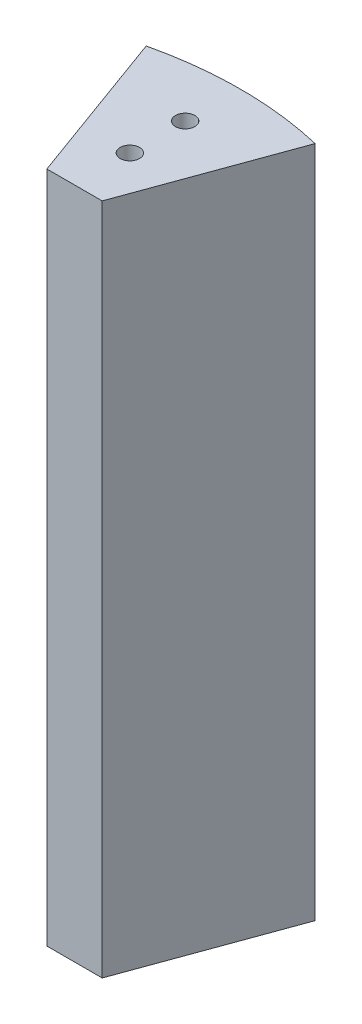
SolidWorks part; units mm, degrees
ref_plane "Front Plane" through (0, 0, 0) normal (0, 0, 1) x (1, 0, 0)
ref_plane "Top Plane" through (0, 0, 0) normal (0, 1, 0) x (1, 0, 0)
ref_plane "Right Plane" through (0, 0, 0) normal (1, 0, 0) x (0, 0, -1)
sketch "Sketch1" plane through (0, 0, 0) normal (0, 1, 0) x (1, 0, 0)
  line L0 (0, 0) -> (0, 66.5)
  line L1 (0, 0) -> (57.5907, -33.25)
  line L2 (0, 0) -> (-57.5907, -33.25)
  line L3 (5, 36.5) -> (-5, 36.5)
  line L4 (-5, 36.5) -> (-15.2722, 64.7226)
  line L5 (5, 36.5) -> (15.2722, 64.7226)
  line L6 (0, 66.5) -> (0, 56.5)
  line L7 (0, 56.5) -> (0, 46.5)
  line L8 (34.1099, -13.9199) -> (63.6875, -19.1352)
  line L9 (29.1099, -22.5801) -> (34.1099, -13.9199)
  line L10 (29.1099, -22.5801) -> (48.4153, -45.5874)
  line L11 (-29.1099, -22.5801) -> (-48.4153, -45.5874)
  line L12 (-34.1099, -13.9199) -> (-29.1099, -22.5801)
  line L13 (-34.1099, -13.9199) -> (-63.6875, -19.1352)
  circle A0 centre (0, 0) radius 66.5
  circle A1 centre (0, 56.5) radius 1.75
  circle A2 centre (0, 46.5) radius 1.75
  circle A3 centre (40.2702, -23.25) radius 1.75
  circle A4 centre (48.9304, -28.25) radius 1.75
  circle A5 centre (-40.2702, -23.25) radius 1.75
  circle A6 centre (-48.9304, -28.25) radius 1.75
  point P9 (0, 36.5)
  point P15 (-28.7953, -16.625)
  point P34 (0, 0)
  dimension "D1" = 133
  dimension "D10" = 3.5
  dimension "D2" = 120
  dimension "D3" = 120
  dimension "D4" = 10
  dimension "D5" = 110
  dimension "D6" = 110
  dimension "D7" = 30
  dimension "D8" = 10
  dimension "D9" = 10
  dimension "D11" = 3
extrude "Boss-Extrude1" add sketch "Sketch1" along normal blind 121.65 contours A2 L7 A1 L6 A0 L4 L3 L0 | A2 L0 L3 L5 A0 L6 A1 L7
